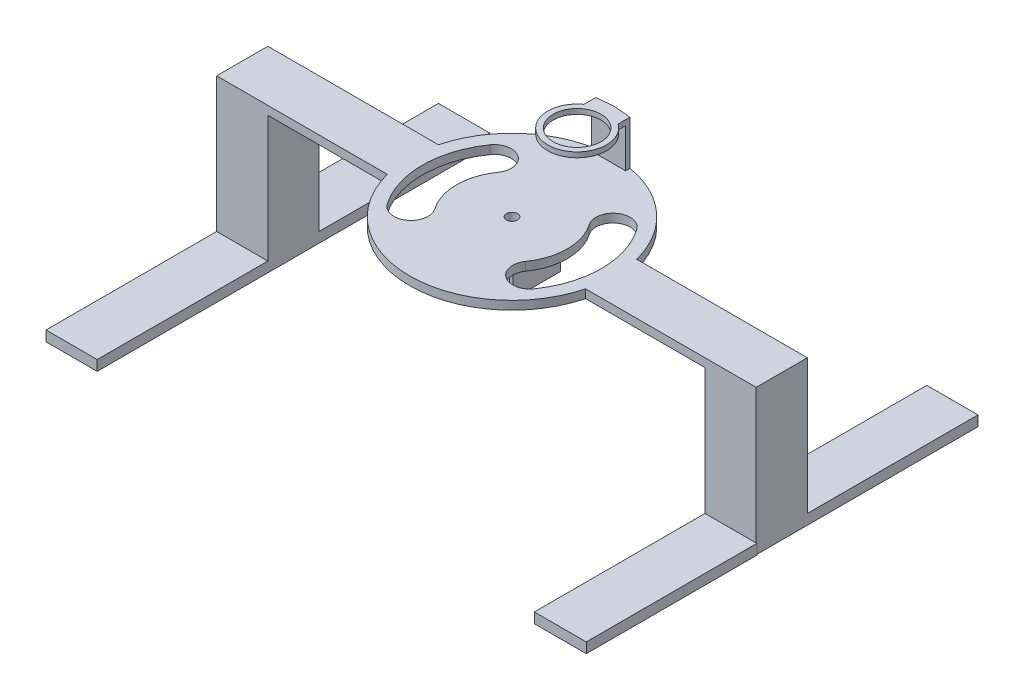
SolidWorks part; units mm, degrees
material "Custom Plastic"
ref_plane "Front Plane" through (0, 0, 0) normal (0, 0, 1) x (1, 0, 0)
ref_plane "Top Plane" through (0, 0, 0) normal (0, 1, 0) x (1, 0, 0)
ref_plane "Right Plane" through (0, 0, 0) normal (1, 0, 0) x (0, 0, -1)
sketch "Sketch1" plane through (0, 0, 0) normal (0, 1, 0) x (1, 0, 0)
  circle A0 centre (0, 0) radius 60
  dimension "D1" = 120
extrude "Boss-Extrude1" add sketch "Sketch1" along normal blind 5
sketch "Sketch2" plane through (0, 5, 0) normal (0, 1, 0) x (1, 0, 0)
  line L2 (0, 0) -> (34.814, 24.377) construction
  line L3 (-2.75, 0) -> (2.75, 0) construction
  line L4 (-26.6224, 18.6412) -> (-34.814, 24.377) construction
  line L5 (-26.6224, -18.6412) -> (-34.814, -24.377) construction
  line L6 (0, 0) -> (34.814, -24.377) construction
  arc A2 (-43.0055, 30.1128) -> (-43.0055, -30.1128) centre (0, 0) ccw
  arc A3 (-26.6224, 18.6412) -> (-26.6224, -18.6412) centre (0, 0) ccw
  arc A4 (-26.6224, 18.6412) -> (-43.0055, 30.1128) centre (-34.814, 24.377) ccw
  arc A5 (-43.0055, -30.1128) -> (-26.6224, -18.6412) centre (-34.814, -24.377) ccw
  arc A6 (43.0055, 30.1128) -> (26.6224, 18.6412) centre (34.814, 24.377) ccw
  arc A7 (26.6224, -18.6412) -> (43.0055, -30.1128) centre (34.814, -24.377) ccw
  arc A8 (26.6224, -18.6412) -> (26.6224, 18.6412) centre (0, 0) ccw
  arc A9 (43.0055, -30.1128) -> (43.0055, 30.1128) centre (0, 0) ccw
  dimension "D1" = 105
  dimension "D2" = 65
  dimension "D7" = 20
  dimension "D8" = 20
  dimension "D9" = 20
  dimension "D10" = 20
  dimension "D11" = 35
  dimension "D3" = 42.5
  dimension "D4" = 42.5
  dimension "D5" = 42.5
  dimension "D6" = 42.5
  dimension "D12" = 35
  dimension "D13" = 35
  dimension "D14" = 35
extrude "Cut-Extrude1" cut sketch "Sketch2" against normal blind 5
sketch "Sketch3" plane through (0, 5, 0) normal (0, 1, 0) x (1, 0, 0)
  line L0 (10, 56.6238) -> (10, 59.1608)
  line L2 (0, -2.75) -> (0, 2.75) construction
  line L3 (-10, 56.6238) -> (-10, 59.1608)
  line L4 (-10, 56.6238) -> (10, 56.6238)
  line L5 (-10, 0) -> (-10, 67.7783) construction
  line L6 (10, 0) -> (10, 67.7783) construction
  arc A0 (10, 59.1608) -> (-10, 59.1608) centre (0, 0) ccw
  dimension "D4" = 120
  dimension "D2" = 10
  dimension "D5" = 20
  dimension "D3" = 20
extrude "Boss-Extrude2" add sketch "Sketch3" along normal blind 23
sketch "Sketch4" plane through (0, 5, 0) normal (0, 1, 0) x (1, 0, 0)
  circle A0 centre (0, 0) radius 3.25
  dimension "D1" = 6.5
extrude "Cut-Extrude2" cut sketch "Sketch4" against normal blind 15
sketch "Sketch5" plane through (0, 5, 0) normal (0, 1, 0) x (1, 0, 0)
  line L0 (-58.0948, 15) -> (-158.0948, 15)
  line L2 (-58.0948, -15) -> (-158.0948, -15)
  line L3 (-158.0948, 15) -> (-158.0948, -15)
  arc A0 (-58.0948, 15) -> (-58.0948, -15) centre (0, 0) ccw
  dimension "D4" = 120
  dimension "D1" = 100
  dimension "D3" = 30
extrude "Boss-Extrude3" add sketch "Sketch5" against normal blind 5
mirror "Mirror1" about plane through (0, 0, 0) normal (1, 0, 0) of "Boss-Extrude3"
sketch "Sketch6" plane through (0, 0, 0) normal (0, -1, 0) x (1, 0, 0)
  line L0 (-58.0948, -15) -> (-158.0948, -15) construction
  line L1 (-158.0948, 15) -> (-128.0948, 15)
  line L2 (-158.0948, 15) -> (-158.0948, -15)
  line L3 (-158.0948, -15) -> (-128.0948, -15)
  line L4 (-128.0948, 15) -> (-128.0948, -15)
  dimension "D1" = 30
  dimension "D2" = 30
extrude "Boss-Extrude4" add sketch "Sketch6" along normal blind 80
mirror "Mirror2" about plane through (0, 0, 0) normal (1, 0, 0) of "Boss-Extrude4"
sketch "Sketch10" plane through (0, 28, 0) normal (0, 1, 0) x (1, 0, 0)
  line L0 (0, -59.4) -> (0, 59.4) construction
  line L1 (-10, 56.6238) -> (10, 56.6238) construction
  line L2 (-10, 59.1608) -> (-10, 52.168)
  line L3 (-10, 59.1608) -> (0, 60)
  line L4 (0, 60) -> (10, 59.1608)
  line L5 (10, 59.1608) -> (10, 52.168)
  circle A0 centre (0, 38.1738) radius 14
  arc A1 (10, 59.1608) -> (-10, 59.1608) centre (0, 0) ccw construction
  arc A2 (-10, 52.168) -> (10, 52.168) centre (0, 38.1738) ccw
  point P17 (10, 56.6238)
  point P19 (0, 0)
  line M2 (-10, 56.6238) -> (10, 56.6238)
  line M3 (10, 56.6238) -> (10, 59.1608)
  line M5 (-10, 59.1608) -> (-10, 56.6238)
  dimension "D1" = 28
  dimension "D2" = 18.45
  dimension "D3" = 3.2
extrude "Boss-Extrude6" add sketch "Sketch10" along normal blind 3 contours A2 A0 M2 | L4 L3 M5 M2 M3
sketch "Sketch12" plane through (0, -80, 0) normal (0, -1, 0) x (1, 0, 0)
  line L0 (128.0948, -15) -> (-128.0948, -15) construction
  line L6 (-158.0948, -15) -> (-128.0948, -15)
  line L7 (-158.0948, -15) -> (-158.0948, -115)
  line L8 (-158.0948, -115) -> (-128.0948, -115)
  line L9 (-128.0948, -15) -> (-128.0948, -115)
  line L10 (-128.0948, 15) -> (-158.0948, 15)
  line L11 (-128.0948, 15) -> (-128.0948, 115)
  line L12 (-128.0948, 115) -> (-158.0948, 115)
  line L13 (-158.0948, 15) -> (-158.0948, 115)
  line L14 (128.0948, 15) -> (158.5166, 15)
  line L18 (158.0948, -15) -> (128.0948, -15)
  line L19 (158.0948, -15) -> (158.0948, -115)
  line L20 (158.0948, -115) -> (128.0948, -115)
  line L21 (128.0948, -15) -> (128.0948, -115)
  line L22 (158.5166, 15) -> (128.0948, 15)
  line L23 (158.5166, 15) -> (158.5166, 115)
  line L24 (158.5166, 115) -> (128.0948, 115)
  line L25 (128.0948, 15) -> (128.0948, 115)
  line M2 (158.0948, 15) -> (128.0948, 15)
  line M4 (128.0948, -15) -> (158.0948, -15)
  dimension "D1" = 100
  dimension "D2" = 100
sketch "Sketch7" plane through (0, 0, 0) normal (0, -1, 0) x (1, 0, 0)
  line L0 (0, 6.5) -> (0, -17.5) construction
  line L5 (-7, 6.5) -> (7, 6.5)
  line L6 (-7, 6.5) -> (-7, -17.5)
  line L7 (-7, -17.5) -> (7, -17.5)
  line L8 (7, 6.5) -> (7, -17.5)
  line L9 (-9, 8.5) -> (9, 8.5)
  line L14 (9, 8.5) -> (9, -19.5)
  line L15 (9, -19.5) -> (-9, -19.5)
  line L16 (-9, -19.5) -> (-9, 8.5)
  point P0 (0, 0)
  point P12 (0, -5.5)
  dimension "D1" = 6.5
  dimension "D2" = 24
  dimension "D3" = 14
  dimension "D4" = 2
  dimension "D5" = 2
  dimension "D6" = 2
  dimension "D7" = 2
extrude "Boss-Extrude9" add sketch "Sketch7" along normal blind 28 contours L16 L15 L14 L9 L5 L8 L7 L6
sketch "Sketch15" plane through (0, 0, 8.5) normal (0, 0, 1) x (1, 0, 0)
  line L5 (0, -59.4) -> (0, 59.4) construction
  line L6 (7, -26) -> (-7, -26)
  line L7 (7, -26) -> (7, 0)
  line L8 (7, 0) -> (-7, 0)
  line L9 (-7, -26) -> (-7, 0)
  line L10 (7, -26) -> (-7, 0) construction
  line L11 (7, 0) -> (-7, -26) construction
  line L12 (-9, 0) -> (9, 0) construction
  line L13 (-9, -28) -> (9, -28) construction
  line L14 (9, -28) -> (9, 0) construction
  point P0 (0, -13)
  dimension "D1" = 2
  dimension "D2" = 2
extrude "Cut-Extrude3" cut sketch "Sketch15" against normal offset from surface (26 mm away) 2 contours L9 L8 L7 L6 up to face at (0, -14, -19.5)
sketch "Sketch16" plane through (0, 0, -17.5) normal (0, 0, 1) x (1, 0, 0)
  line L0 (7, -26) -> (7, 0) construction
  line L1 (-7, 0) -> (7, 0)
  line L2 (-7, 0) -> (-7, -10)
  line L3 (-7, -10) -> (7, -10)
  line L4 (7, 0) -> (7, -10)
  line L5 (7, -26) -> (-7, -26) construction
  dimension "D1" = 16
extrude "Cut-Extrude4" cut sketch "Sketch16" against normal blind 2
extrude "Boss-Extrude11" add sketch "Sketch12" against normal blind 6 contours L25 L14 L23 L24 M2 | L21 L20 L19 M4 | L13 L10 L11 L12 | L7 L8 L9 L6
ref_plane "Plane1" through (0, 0, -60) normal (0, 0, -1) x (-1, 0, 0)
sketch "Sketch17" plane through (0, 0, -60) normal (0, 0, -1) x (-1, 0, 0)
  circle A0 centre (0, 15) radius 3.5
  point P2 (0, 0)
  dimension "D1" = 7
  dimension "D2" = 15
extrude "Cut-Extrude5" cut sketch "Sketch17" against normal blind 1.5
